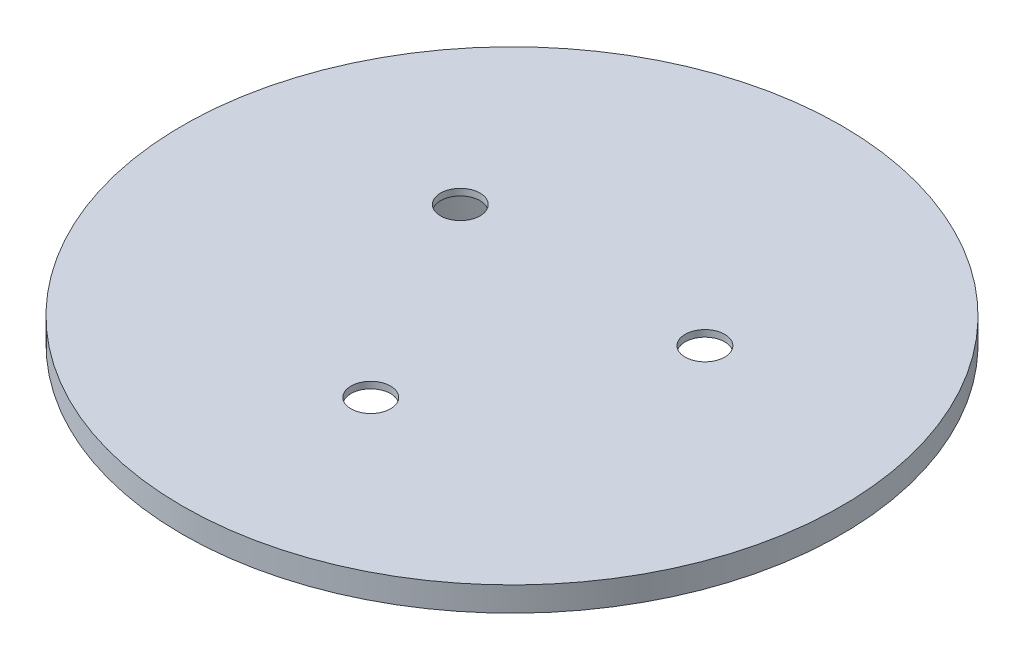
SolidWorks part; units mm, degrees
other "Markup1"
sketch "Sketch5" plane through (35, 0, 35) normal (0.1915, -0.9537, 0.2321) x (0.8995, 0.2651, 0.3474)
sketch "Sketch6" plane through (35, 0, 35) normal (0.1915, -0.9537, 0.2321) x (0.8995, 0.2651, 0.3474)
ref_plane "Front Plane" through (0, 0, 0) normal (0, 0, 1) x (1, 0, 0)
ref_plane "Top Plane" through (0, 0, 0) normal (0, 1, 0) x (1, 0, 0)
ref_plane "Right Plane" through (0, 0, 0) normal (1, 0, 0) x (0, 0, -1)
sketch "Sketch1" plane through (0, 0, 0) normal (0, 1, 0) x (1, 0, 0)
  circle A0 centre (0, 0) radius 24.8
  dimension "D1" = 49.6
extrude "Boss-Extrude1" add sketch "Sketch1" along normal blind 3.1
sketch "Sketch2" plane through (0, 3.1, 0) normal (0, 1, 0) x (1, 0, 0)
  circle A0 centre (0, 0) radius 35
  dimension "D1" = 70
extrude "Boss-Extrude2" add sketch "Sketch2" along normal blind 2.6
sketch "Sketch3" plane through (0, 0, 0) normal (0, -1, 0) x (1, 0, 0)
  circle A0 centre (0, 0) radius 20.05
  dimension "D1" = 40.1
extrude "Cut-Extrude1" cut sketch "Sketch3" against normal blind 5
sketch "Sketch4" plane through (0, 5, 0) normal (0, -1, 0) x (1, 0, 0)
  line L0 (0, 0) -> (0, 15) construction
  line L1 (0, 0) -> (12.9904, -7.5) construction
  line L2 (0, 0) -> (-12.9904, -7.5) construction
  circle A0 centre (0, 0) radius 15 construction
  circle A1 centre (0, 0) radius 20.05
  circle A2 centre (0, 0) radius 20.05
  circle A3 centre (0, 15) radius 2.1
  circle A4 centre (-12.9904, -7.5) radius 2.1
  circle A5 centre (12.9904, -7.5) radius 2.1
  dimension "D2" = 30
  dimension "D5" = 4.2
  dimension "D3" = 120
  dimension "D4" = 120
  dimension "D1" = 0
extrude "Cut-Extrude2" cut sketch "Sketch4" against normal up to next contours A0 | A3 | A4 | A5
